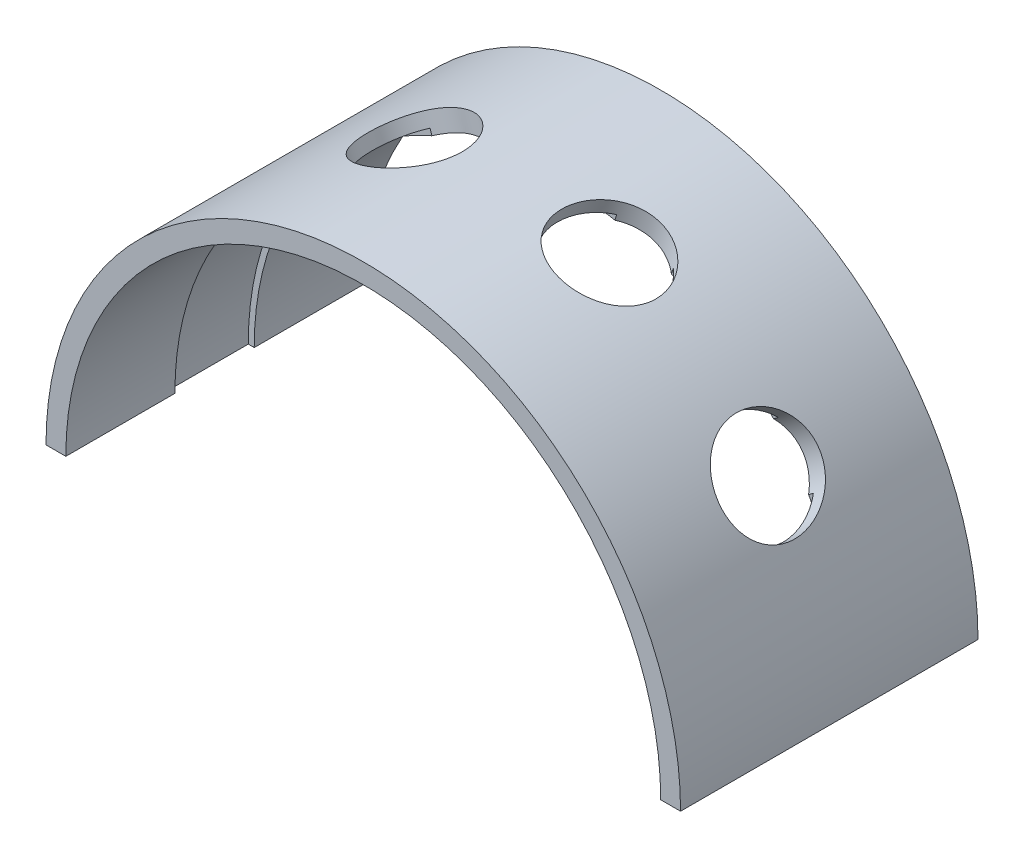
SolidWorks part; units mm, degrees
material "Plain Carbon Steel"
ref_plane "Front Plane" through (0, 0, 0) normal (0, 0, 1) x (1, 0, 0)
ref_plane "Top Plane" through (0, 0, 0) normal (0, 1, 0) x (1, 0, 0)
ref_plane "Right Plane" through (0, 0, 0) normal (1, 0, 0) x (0, 0, -1)
sketch "Sketch1" plane through (0, 0, 0) normal (0, 0, 1) x (1, 0, 0)
  arc A0 (-16, 0) -> (16, 0) centre (0, 0) cw
  dimension "D1" = 16
sketch "Sketch2" plane through (0, 0, 0) normal (0, 1, 0) x (1, 0, 0)
  line L0 (-15, -7.5) -> (-15, -2)
  line L1 (-15, -2) -> (-15.3, -2)
  line L2 (-15.3, -2) -> (-15.3, 2)
  line L3 (-15.3, 2) -> (-15, 2)
  line L4 (-15, 2) -> (-15, 7.5)
  line L5 (-15, 7.5) -> (-16, 7.5)
  line L6 (-16, 7.5) -> (-16, -7.5)
  line L7 (-16, -7.5) -> (-15, -7.5)
  point P3 (-16, 0)
  dimension "D1" = 15
  dimension "D2" = 15
  dimension "D3" = 0.7
  dimension "D4" = 4
sweep "Sweep1" add profiles "Sketch2" path "Sketch1"
sketch "Sketch3" plane through (0, 0, 0) normal (0, 0, 1) x (1, 0, 0)
  line L0 (0, 0) -> (0, 19.4491) construction
  line L1 (0, 0) -> (6.3285, 19.477) construction
  line L2 (0, 0) -> (-6.4321, 19.796) construction
  line L3 (0, 0) -> (-18.2798, 13.281) construction
  line L4 (0, 0) -> (17.3766, 12.6249) construction
  line L5 (9.8198, 7.1345) -> (15.3759, 11.1712)
  line L6 (15.3759, 11.1712) -> (16.8454, 9.1487)
  line L7 (16.8454, 9.1487) -> (11.2892, 5.1119)
  line L8 (11.2892, 5.1119) -> (9.8198, 7.1345)
  dimension "D1" = 18
  dimension "D2" = 36
  dimension "D3" = 36
  dimension "D4" = 36
  dimension "D5" = 2.5
revolve "Cut-Revolve1" cut sketch "Sketch3" angle 360 about L5
ref_axis "Axis1" through (0, 0, -11.55) along (0, 0, 1)
pattern_circular "CirPattern1" count 4 over 108 about axis through (0, 0, -11.55) along (0, 0, 1) of "Cut-Revolve1"
